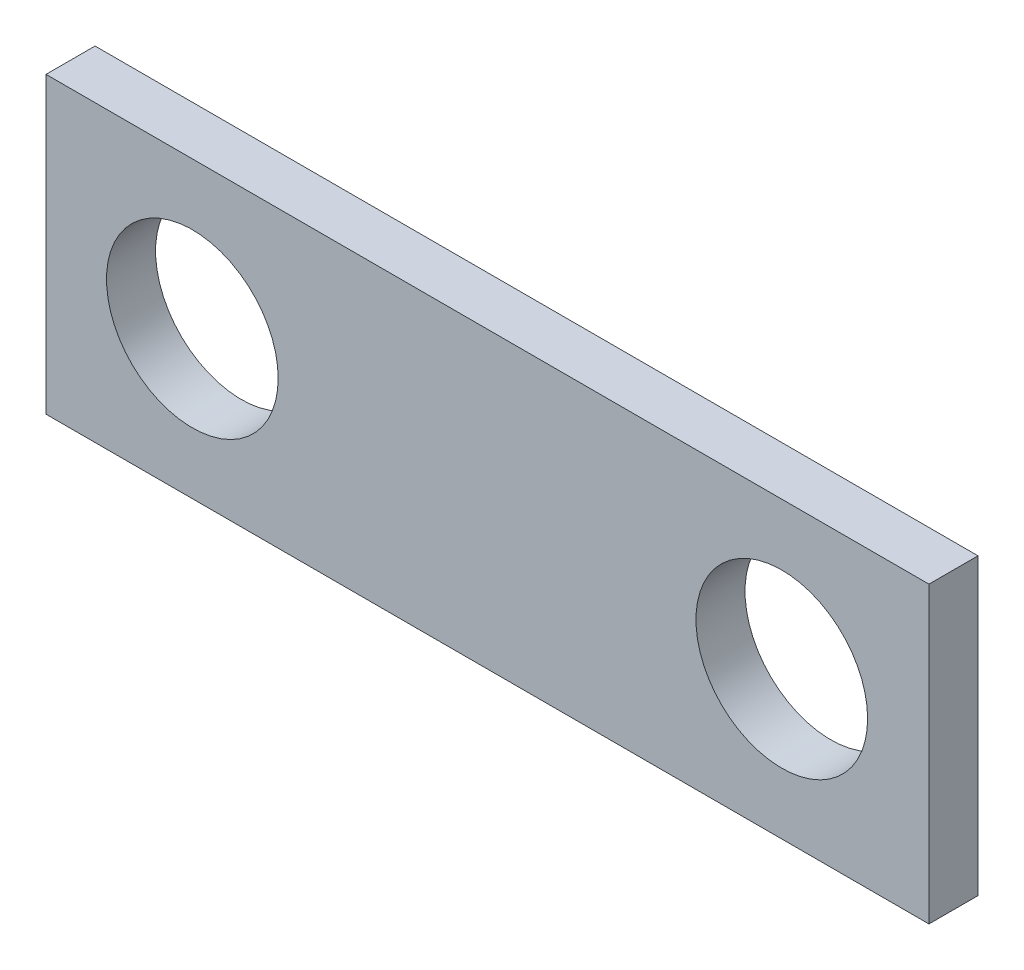
SolidWorks part; units mm, degrees
ref_plane "Front Plane" through (0, 0, 0) normal (0, 0, 1) x (1, 0, 0)
ref_plane "Top Plane" through (0, 0, 0) normal (0, 1, 0) x (1, 0, 0)
ref_plane "Right Plane" through (0, 0, 0) normal (1, 0, 0) x (0, 0, -1)
sketch "Sketch1" plane through (0, 0, 0) normal (0, 0, 1) x (1, 0, 0)
  line L1 (-57.15, -19.05) -> (57.15, -19.05)
  line L2 (-57.15, -19.05) -> (-57.15, 19.05)
  line L3 (-57.15, 19.05) -> (57.15, 19.05)
  line L4 (57.15, -19.05) -> (57.15, 19.05)
  line L5 (-57.15, -19.05) -> (57.15, 19.05) construction
  line L6 (-57.15, 19.05) -> (57.15, -19.05) construction
  point P0 (0, 0)
  dimension "D1" = 38.1
  dimension "D2" = 114.3
extrude "Boss-Extrude1" add sketch "Sketch1" along normal blind 6.35
sketch "Sketch2" plane through (0, 0, 6.35) normal (0, 0, 1) x (1, 0, 0)
  line L0 (0, 0) -> (-38.2053, 0) construction
  line L1 (0, 0) -> (38.1, 0) construction
  circle A0 centre (-38.2053, 0) radius 11.1125
  circle A1 centre (38.1, 0) radius 11.1125
  dimension "D3" = 22.225
  dimension "D4" = 22.225
  dimension "D1" = 38.2053
  dimension "D2" = 38.1
extrude "Cut-Extrude1" cut sketch "Sketch2" against normal through all
